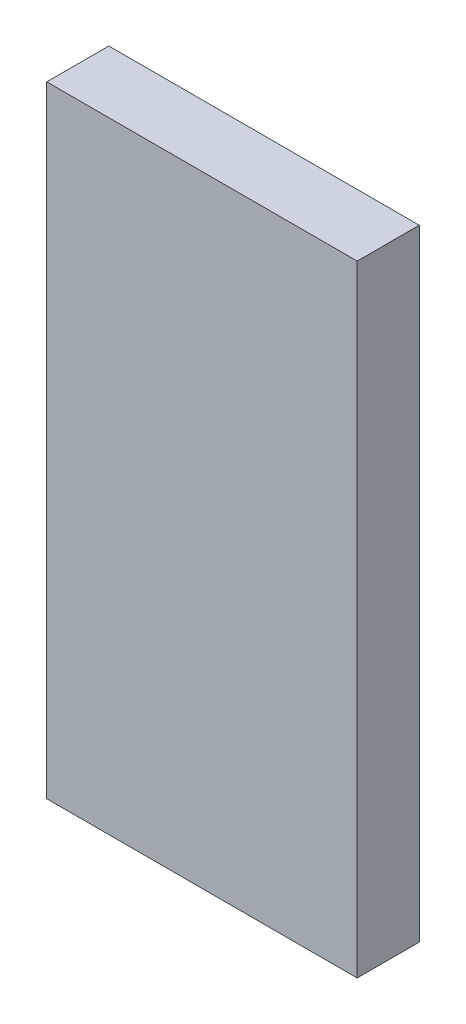
SolidWorks part; units mm, degrees
material "Tungsten"
ref_plane "Front Plane" through (0, 0, 0) normal (0, 0, 1) x (1, 0, 0)
ref_plane "Top Plane" through (0, 0, 0) normal (0, 1, 0) x (1, 0, 0)
ref_plane "Right Plane" through (0, 0, 0) normal (1, 0, 0) x (0, 0, -1)
sketch "Sketch2" plane through (0, 0, 0) normal (0, 0, 1) x (1, 0, 0)
  line L0 (30, 0) -> (-30, 0)
  line L1 (30, 0) -> (30, 120)
  line L2 (-30, 0) -> (-30, 120)
  line L3 (-30, 120) -> (30, 120)
  point P4 (0, 0)
  dimension "D1" = 120
  dimension "D2" = 60
extrude "Boss-Extrude1" add sketch "Sketch2" along normal blind 12
